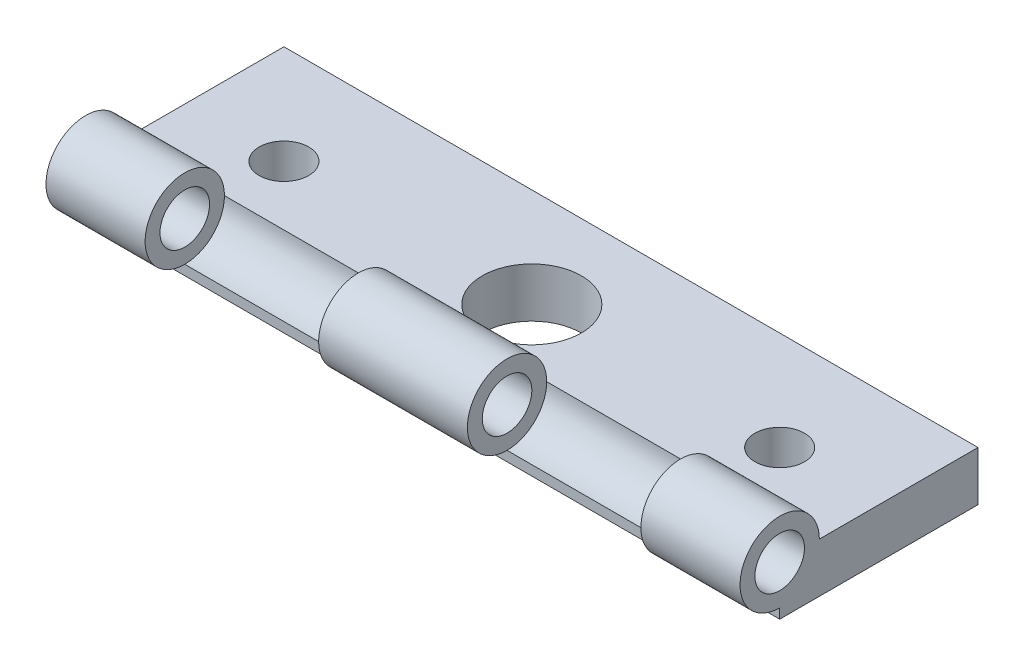
SolidWorks part; units mm, degrees
ref_plane "Front Plane" through (0, 0, 0) normal (0, 0, 1) x (1, 0, 0)
ref_plane "Top Plane" through (0, 0, 0) normal (0, 1, 0) x (1, 0, 0)
ref_plane "Right Plane" through (0, 0, 0) normal (1, 0, 0) x (0, 0, -1)
sketch "Sketch2" plane through (0, 0, 0) normal (0, 1, 0) x (1, 0, 0)
  line L1 (-44.45, 0) -> (44.45, 0)
  line L2 (-44.45, 0) -> (-44.45, 25.4)
  line L3 (-44.45, 25.4) -> (44.45, 25.4)
  line L4 (44.45, 0) -> (44.45, 25.4)
  line L5 (-44.45, 0) -> (44.45, 25.4) construction
  line L6 (-44.45, 25.4) -> (44.45, 0) construction
  circle A0 centre (-31.75, 12.7) radius 3.175
  circle A1 centre (0, 12.7) radius 6.35
  circle A2 centre (31.75, 12.7) radius 3.175
  point P0 (0, 12.7)
  dimension "D5" = 6.35
  dimension "D6" = 12.7
  dimension "D1" = 25.4
  dimension "D2" = 63.5
  dimension "D3" = 31.75
  dimension "D4" = 88.9
extrude "Boss-Extrude1" add sketch "Sketch2" along normal blind 6.35
sketch "Sketch3" plane through (-44.45, 0, 0) normal (-1, 0, 0) x (0, 0, 1)
  circle A0 centre (0, 6.35) radius 5.08
  dimension "D1" = 10.16
extrude "Cut-Extrude1" cut sketch "Sketch3" against normal through all
sketch "Sketch4" plane through (-44.45, 0, 0) normal (-1, 0, 0) x (0, 0, 1)
  circle A0 centre (0, 6.35) radius 3.175
  arc A2 (-5.08, 6.35) -> (0, 1.27) centre (0, 6.35) ccw construction
  circle A3 centre (0, 6.35) radius 5.08
  dimension "D1" = 6.35
extrude "Boss-Extrude2" add sketch "Sketch4" against normal blind 12.7
mirror "Mirror1" about plane through (0, 0, 0) normal (1, 0, 0) of "Boss-Extrude2"
sketch "Sketch5" plane through (0, 0, 0) normal (1, 0, 0) x (0, 0, -1)
  circle A0 centre (0, 6.35) radius 3.175 construction
  circle A1 centre (0, 6.35) radius 3.175
  circle A2 centre (0, 6.35) radius 5.08
  arc A3 (5.08, 6.35) -> (0, 1.27) centre (0, 6.35) ccw construction
extrude "Boss-Extrude3" add sketch "Sketch5" along normal mid plane 19.05
equation "\"D3@Sketch2\"=\"D2@Sketch2\"/2"
